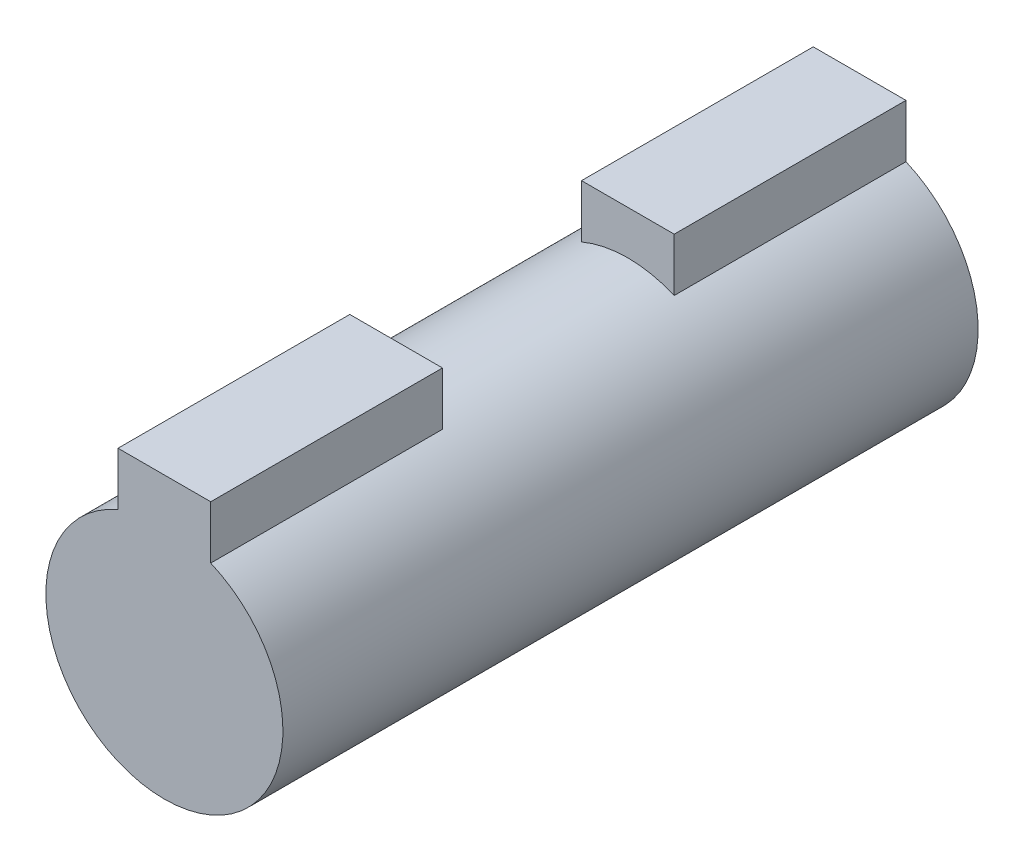
SolidWorks part; units mm, degrees
material "Alloy Steel (SS)"
ref_plane "Front " through (0, 0, 0) normal (0, 0, 1) x (1, 0, 0)
ref_plane "Top " through (0, 0, 0) normal (0, 1, 0) x (1, 0, 0)
ref_plane "Right " through (0, 0, 0) normal (1, 0, 0) x (0, 0, -1)
sketch "Sketch1" plane through (0, 0, 0) normal (0, 0, 1) x (1, 0, 0)
  line L0 (0, 0) -> (0, 8.566) construction
  line L2 (2, 7) -> (-2, 7)
  line L3 (2, 7) -> (2, 4.7072)
  line L5 (-2, 7) -> (-2, 4.7072)
  arc A0 (-2, 4.7072) -> (2, 4.7072) centre (0, 0) ccw
  dimension "D1" = 10.229
  dimension "D2" = 4
  dimension "D3" = 7
extrude "Boss-Extrude1" add sketch "Sketch1" along normal blind 30
sketch "Sketch2" plane through (0, 0, 30) normal (0, 0, 1) x (1, 0, 0)
  circle A0 centre (0, 0) radius 5.1145
  circle A1 centre (0, 0) radius 7.4911
extrude "Cut-Extrude1" cut sketch "Sketch2" against normal blind 10 from offset 10
